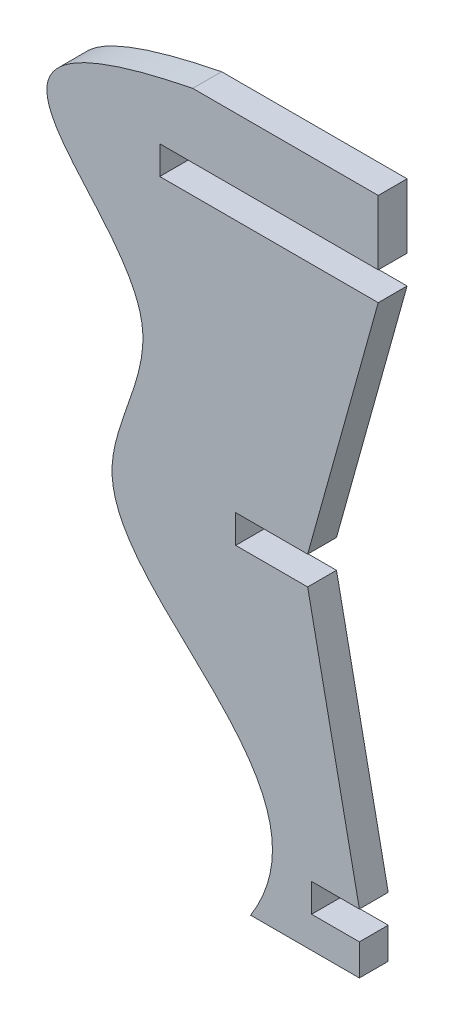
SolidWorks part; units mm, degrees
ref_plane "Piano frontale" through (0, 0, 0) normal (0, 0, 1) x (1, 0, 0)
ref_plane "Piano superiore" through (0, 0, 0) normal (0, 1, 0) x (1, 0, 0)
ref_plane "Piano destro" through (0, 0, 0) normal (1, 0, 0) x (0, 0, -1)
sketch "Model" plane through (0, 0, 0) normal (0, 0, 1) x (1, 0, 0)
  line L0 (-15.591, -6.0983) -> (-37.0752, -6.0983)
  line L1 (-15.591, 0.09) -> (-15.591, -6.0983)
  line L2 (-15.591, 0.09) -> (-25.0225, 0.09)
  line L3 (-25.0225, 0.09) -> (-25.0225, 5.7)
  line L4 (-25.0225, 5.7) -> (-15.591, 5.7)
  line L5 (-15.591, 5.7) -> (-25.8057, 55.7)
  line L6 (-25.8057, 55.7) -> (-40.0225, 55.7)
  line L7 (-40.0225, 55.7) -> (-40.0225, 61.31)
  line L8 (-40.0225, 61.31) -> (-25.8057, 61.31)
  line L9 (-25.8057, 61.31) -> (-11.8621, 111.31)
  line L10 (-11.8621, 111.31) -> (-55.0225, 111.31)
  line L11 (-55.0225, 111.31) -> (-55.0225, 116.92)
  line L12 (-55.0225, 116.92) -> (-11.8621, 116.92)
  line L13 (-11.8621, 116.92) -> (-11.8621, 129.6505)
  line L14 (-11.8621, 129.6505) -> (-48.5079, 129.6505)
  spline S0 degree 3 poles (-37.0752, -6.0983) (-18.9327, 22.9976) (-82.5226, 39.7803) (-40.9715, 97.4969) (-105.2853, 118.2853) (-48.5079, 129.6505) knots 0 0 0 0 0.428707 0.607446 1 1 1 1
  dimension "D1" = 5.61
  dimension "D2" = 5.61
  dimension "D3" = 5.61
  dimension "D4" = 50
  dimension "D5" = 50
extrude "Estrusione-Estrusione1" add sketch "Model" along normal blind 5.7 contours L10 L11 L12 L13 L14 S0 L0 L1 L2 L3 L4 L5 L6 L7 L8 L9
equation "\"k\"= 0.045mm'kerf"
equation "\"w\"= 30mm'circle width"
equation "\"m\"= 5.7mm'material thickness"
equation "\"jhf\"= \"m\" - 2 * \"k\"'female joint height"
equation "\"jhm\"= \"m\" + 2 * \"k\"'male joint height"
equation "\"d\"= 50mm'circle diameter"
equation "\"d2\"= \"d\" + 30mm"
equation "\"d3\"= \"d2\" + 30mm"
equation "\"id\"= 50mm'internal circle distance"
equation "\"D1@Model\"=\"m\"- 2 * \"k\""
equation "\"D2@Model\"=\"m\"- 2 * \"k\""
equation "\"D3@Model\"=\"m\"- 2 * \"k\""
equation "\"D4@Model\"= \"id\""
equation "\"D5@Model\"=\"id\""
